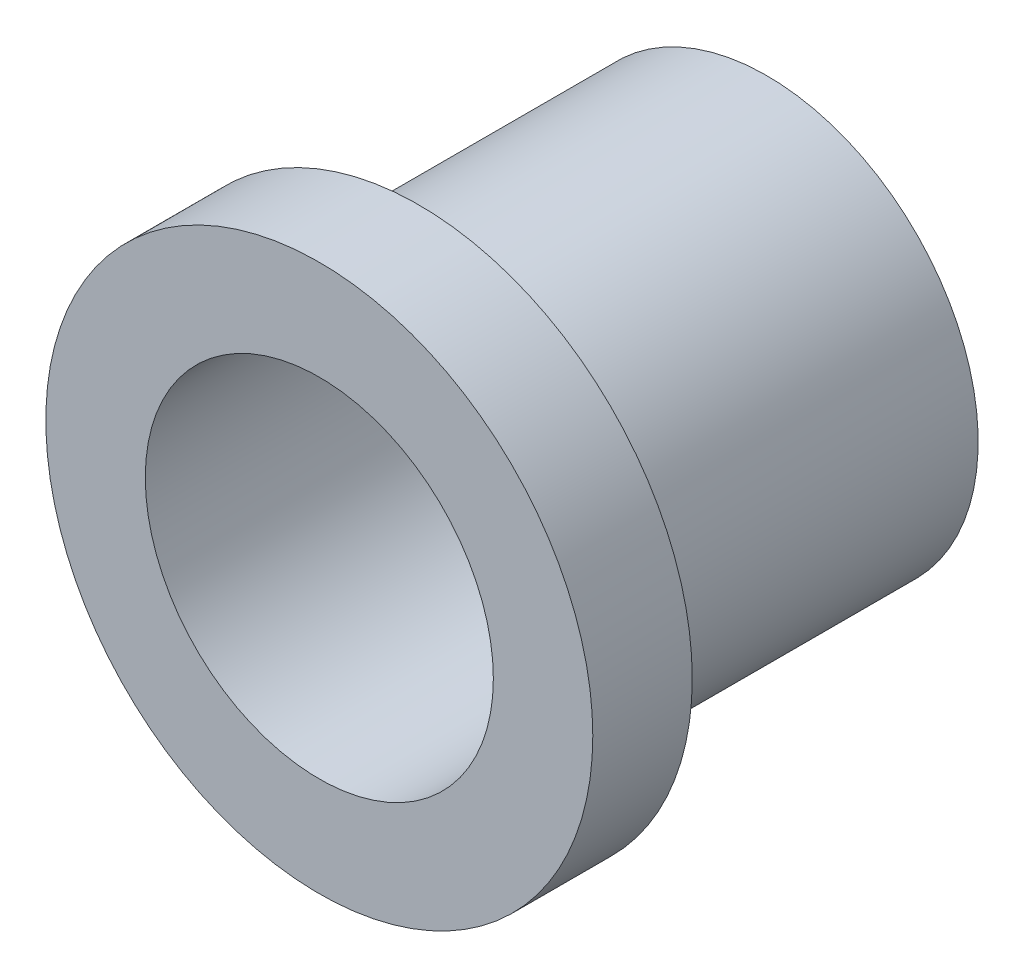
SolidWorks part; units mm, degrees
material "ABS"
ref_plane "Front Plane" through (0, 0, 0) normal (0, 0, 1) x (1, 0, 0)
ref_plane "Top Plane" through (0, 0, 0) normal (0, 1, 0) x (1, 0, 0)
ref_plane "Right Plane" through (0, 0, 0) normal (1, 0, 0) x (0, 0, -1)
sketch "Sketch1" plane through (0, 0, 0) normal (0, 0, 1) x (1, 0, 0)
  circle A0 centre (0, 0) radius 5.5
  dimension "D1" = 11
extrude "Boss-Extrude1" add sketch "Sketch1" against normal blind 2
sketch "Sketch2" plane through (0, 0, -2) normal (0, 0, -1) x (-1, 0, 0)
  circle A0 centre (0, 0) radius 4.25
  dimension "D1" = 8.5
extrude "Boss-Extrude2" add sketch "Sketch2" along normal blind 7
sketch "Sketch5" plane through (0, 0, 0) normal (0, 0, 1) x (1, 0, 0)
  circle A0 centre (0, 0) radius 3.5
  dimension "D1" = 7
extrude "Cut-Extrude3" cut sketch "Sketch5" against normal blind 8
